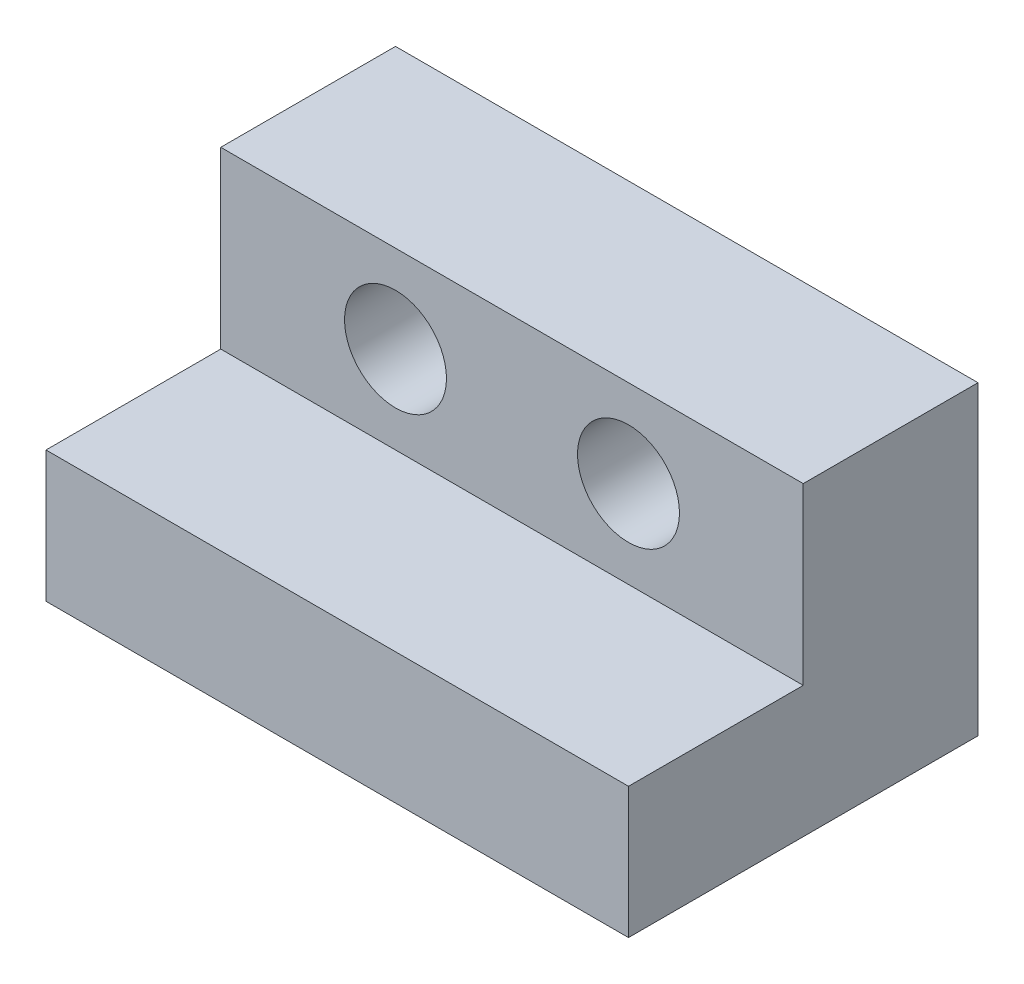
SolidWorks part; units mm, degrees
ref_plane "Front Plane" through (0, 0, 0) normal (0, 0, 1) x (1, 0, 0)
ref_plane "Top Plane" through (0, 0, 0) normal (0, 1, 0) x (1, 0, 0)
ref_plane "Right Plane" through (0, 0, 0) normal (1, 0, 0) x (0, 0, -1)
sketch "Sketch1" plane through (0, 0, 0) normal (0, 0, 1) x (1, 0, 0)
  line L0 (0, 0) -> (21.2889, 0) construction
  line L1 (0, 0) -> (0, 13.0018) construction
  line L2 (-10, -5) -> (10, -5) construction
  line L3 (-10, -5) -> (-10, 5) construction
  line L4 (-10, 5) -> (10, 5) construction
  line L5 (10, -5) -> (10, 5) construction
  line L6 (-10, -5) -> (10, 5) construction
  line L7 (-10, 5) -> (10, -5) construction
  line L8 (-4, 12.5) -> (4, 12.5) construction
  line L10 (-10, 5) -> (10, 5)
  line L11 (-10, 5) -> (-10, 15.5)
  line L12 (-10, 15.5) -> (10, 15.5)
  line L13 (10, 5) -> (10, 15.5)
  circle A0 centre (4, 12.5) radius 1.75
  circle A1 centre (-4, 12.5) radius 1.75
  dimension "D5" = 3.5
  dimension "D1" = 20
  dimension "D2" = 10
  dimension "D3" = 7.5
  dimension "D4" = 6
  dimension "D6" = 10.5
extrude "Boss-Extrude1" add sketch "Sketch1" along normal blind 12
sketch "Sketch2" plane through (0, 0, 12) normal (0, 0, 1) x (1, 0, 0)
  line L0 (10, 5) -> (10, 15.5) construction
  line L1 (-10, 15.5) -> (-10, 5) construction
  line L2 (10, 15.5) -> (-10, 15.5) construction
  line L3 (10, 5) -> (10, 15.5)
  line L4 (-10, 15.5) -> (-10, 5)
  line L5 (10, 15.5) -> (-10, 15.5)
  line L7 (-10, 15.5) -> (10, 15.5)
  line L8 (-10, 15.5) -> (-10, 9.5)
  line L9 (-10, 9.5) -> (10, 9.5)
  line L10 (10, 15.5) -> (10, 9.5)
  circle A0 centre (-4, 12.5) radius 1.75 construction
  circle A1 centre (4, 12.5) radius 1.75 construction
  circle A2 centre (-4, 12.5) radius 1.75
  circle A3 centre (4, 12.5) radius 1.75
  point P12 (-10, 9.4362)
  line M4 (10, 15.5) -> (-10, 15.5)
  line M5 (-10, 15.5) -> (-10, 5)
  circle M7 centre (4, 12.5) radius 1.75
  circle M8 centre (-4, 12.5) radius 1.75
  dimension "D1" = 6
extrude "Cut-Extrude1" cut sketch "Sketch2" against normal blind 6 contours L9 L3 M5 M4 M7 M8
sketch "Sketch3" plane through (0, 5, 0) normal (0, -1, 0) x (1, 0, 0)
  line L0 (0, 0) -> (0, 12) construction
  line L1 (-10, 0) -> (0, 0) construction
  line L2 (0, 12) -> (-10, 12) construction
  line L4 (-10, 0) -> (10, 0)
  line L5 (10, 0) -> (10, 12)
  line L6 (10, 12) -> (-10, 12)
  line L7 (-10, 12) -> (-10, 0)
  line L8 (0, 0) -> (10, 0) construction
  line L9 (10, 0) -> (10, 12) construction
  line L10 (10, 12) -> (0, 12) construction
  line L11 (-10, 12) -> (-10, 0) construction
  circle A0 centre (0, 5) radius 4.25
  point P6 (0, 5)
  point P7 (0, 0)
  point P10 (0, 0)
  point P11 (0, 0)
  point P12 (0, 0)
  point P13 (0, 0)
  point P14 (0, 0)
  point P15 (0, 0)
  point P16 (0, 0)
  dimension "D3" = 8.5
  dimension "D2" = 5
  dimension "D1" = 0
extrude "Cut-Extrude3" cut sketch "Sketch3" against normal blind 3
